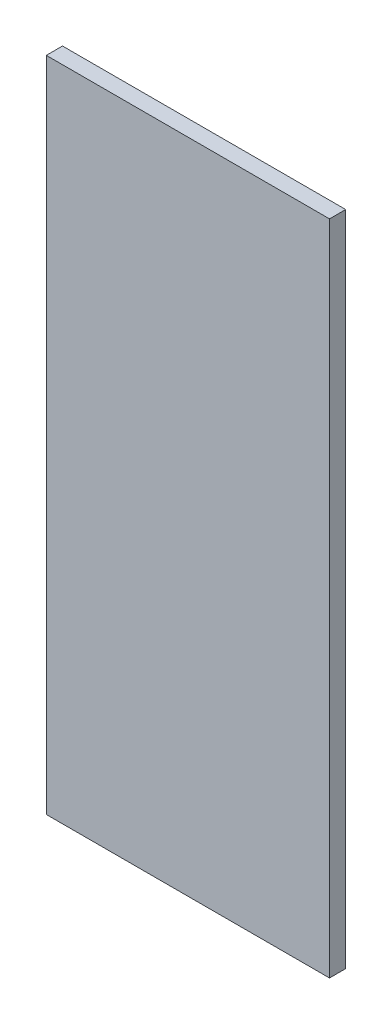
SolidWorks part; units mm, degrees
ref_plane "Front Plane" through (0, 0, 0) normal (0, 0, 1) x (1, 0, 0)
ref_plane "Top Plane" through (0, 0, 0) normal (0, 1, 0) x (1, 0, 0)
ref_plane "Right Plane" through (0, 0, 0) normal (1, 0, 0) x (0, 0, -1)
sketch "Sketch1" plane through (0, 0, 0) normal (0, 0, 1) x (1, 0, 0)
  line L1 (-14, -32.5) -> (14, -32.5)
  line L2 (-14, -32.5) -> (-14, 32.5)
  line L3 (-14, 32.5) -> (14, 32.5)
  line L4 (14, -32.5) -> (14, 32.5)
  line L5 (-14, -32.5) -> (14, 32.5) construction
  line L6 (-14, 32.5) -> (14, -32.5) construction
  point P0 (0, 0)
extrude "Boss-Extrude1" add sketch "Sketch1" against normal blind 1.6
